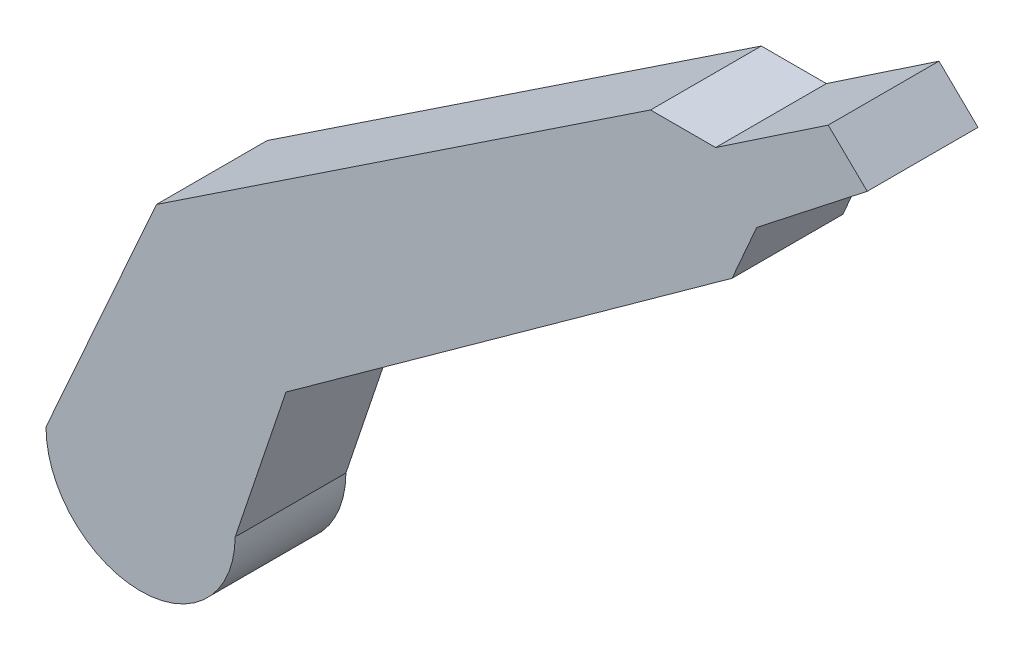
SolidWorks part; units mm, degrees
ref_plane "Front Plane" through (0, 0, 0) normal (0, 0, 1) x (1, 0, 0)
ref_plane "Top Plane" through (0, 0, 0) normal (0, 1, 0) x (1, 0, 0)
ref_plane "Right Plane" through (0, 0, 0) normal (1, 0, 0) x (0, 0, -1)
sketch "Sketch1" plane through (0, 0, 0) normal (0, 0, 1) x (1, 0, 0)
  line L0 (-4.967, 8.8358) -> (-71.885, -35.7072)
  line L1 (-71.885, -35.7072) -> (-86.8336, -69.2613)
  line L2 (6.0778, -5.3822) -> (-54.3404, -48.9366)
  line L3 (-54.3404, -48.9366) -> (-61.2186, -69.3668)
  line L4 (-4.967, 8.8358) -> (3.845, 8.8358)
  line L5 (3.845, 8.8358) -> (19.0919, 19.0919)
  line L6 (19.0919, 19.0919) -> (24.3771, 13.9638)
  line L7 (24.3771, 13.9638) -> (9.408, 2.2454)
  line L8 (9.408, 2.2454) -> (6.0778, -5.3822)
  arc A0 (-86.8336, -69.2613) -> (-61.2186, -69.3668) centre (-74.0261, -69.314) ccw
extrude "Boss-Extrude1" add sketch "Sketch1" against normal blind 15
